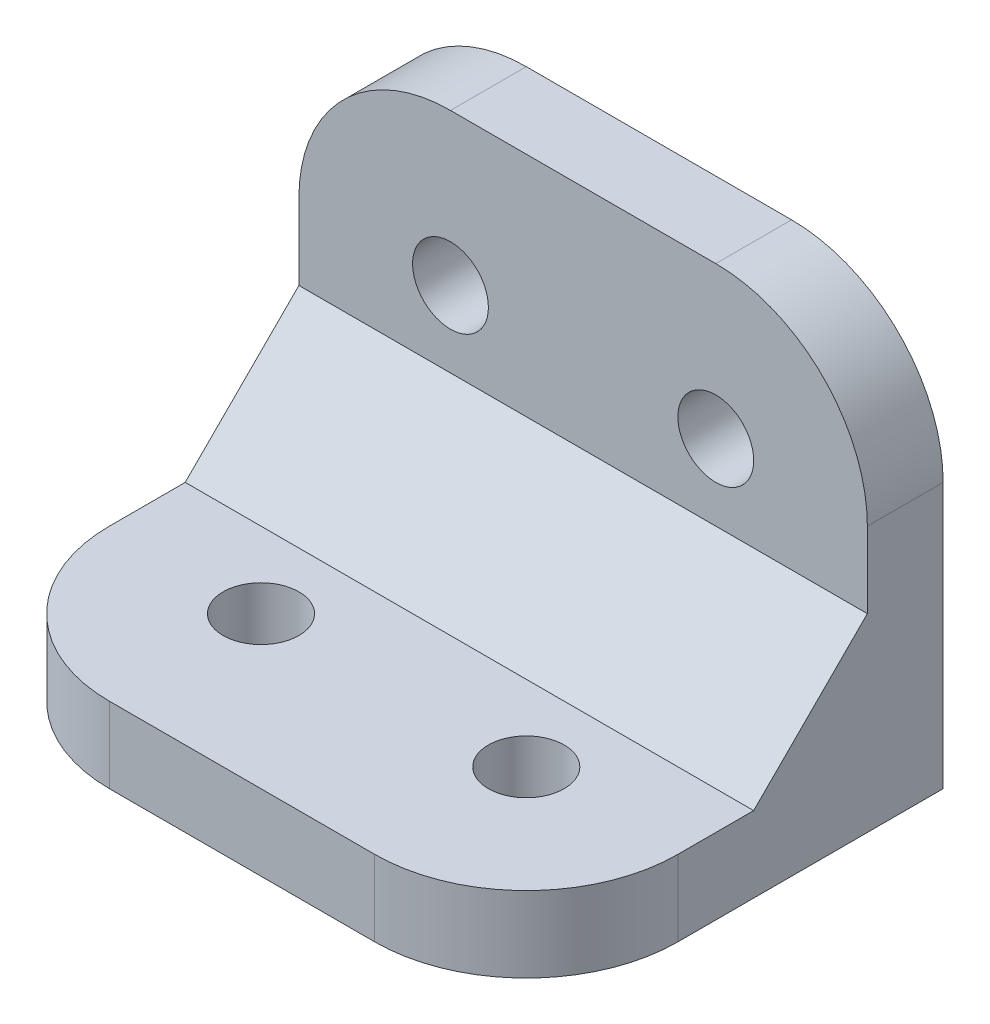
SolidWorks part; units mm, degrees
ref_plane "前视基准面" through (0, 0, 0) normal (0, 0, 1) x (1, 0, 0)
ref_plane "上视基准面" through (0, 0, 0) normal (0, 1, 0) x (1, 0, 0)
ref_plane "右视基准面" through (0, 0, 0) normal (1, 0, 0) x (0, 0, -1)
other "Configuration Table"
sketch "草图1" plane through (0, 0, 0) normal (0, 1, 0) x (1, 0, 0)
  line L1 (0, 0) -> (30, 0)
  line L2 (0, 0) -> (0, -22)
  line L3 (0, -22) -> (30, -22)
  line L4 (30, 0) -> (30, -22)
  dimension "D1" = 22
  dimension "D2" = 30
extrude "凸台-拉伸1" add sketch "草图1" along normal blind 4
sketch "草图2" plane through (0, 4, 0) normal (0, 1, 0) x (1, 0, 0)
  line L0 (30, -22) -> (30, 0) construction
  line L1 (0, 0) -> (30, 0)
  line L2 (0, 0) -> (0, -4)
  line L3 (0, -4) -> (30, -4)
  line L4 (30, 0) -> (30, -4)
  dimension "D1" = 4
extrude "凸台-拉伸2" add sketch "草图2" along normal blind 18
sketch "草图3" plane through (0, 4, 0) normal (0, 1, 0) x (1, 0, 0)
  line L0 (0, -22) -> (30, -22) construction
  line L1 (0, -4) -> (0, -22) construction
  line L2 (30, -22) -> (30, -4) construction
  circle A0 centre (8, -14) radius 2
  circle A1 centre (22, -14) radius 2
  dimension "D1" = 4
  dimension "D2" = 4
  dimension "D3" = 8
  dimension "D4" = 8
  dimension "D5" = 8
  dimension "D6" = 8
extrude "切除-拉伸1" cut sketch "草图3" against normal blind 20
sketch "草图4" plane through (0, 0, 4) normal (0, 0, 1) x (1, 0, 0)
  line L0 (0, 22) -> (0, 4) construction
  line L1 (30, 22) -> (30, 4) construction
  line L2 (0, 22) -> (30, 22) construction
  circle A0 centre (8, 14) radius 2
  circle A1 centre (22, 14) radius 2
  dimension "D1" = 4
  dimension "D2" = 4
  dimension "D3" = 8
  dimension "D4" = 8
  dimension "D5" = 8
  dimension "D6" = 8
extrude "切除-拉伸2" cut sketch "草图4" against normal blind 20
chamfer "倒角1" distance 6 angle 45 1 edges at (15, 4, 4)
fillet "圆角1" radius 8 4 edges at (30, 2, 22) (0, 2, 22) (30, 22, 2) (0, 22, 2)
